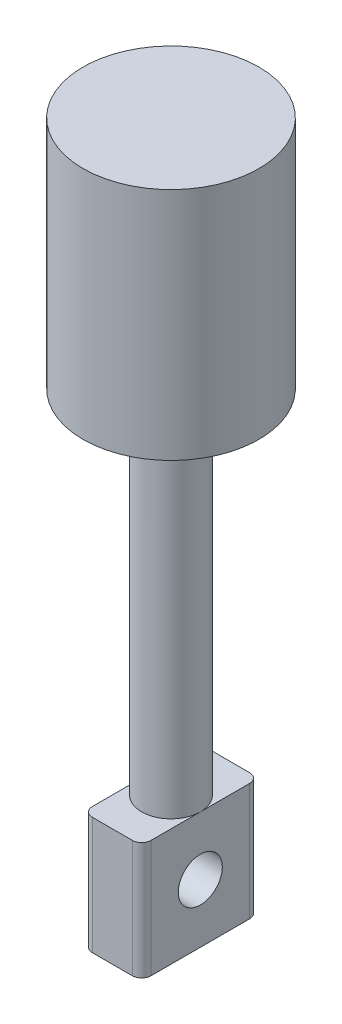
SolidWorks part; units mm, degrees
ref_plane "Front Plane" through (0, 0, 0) normal (0, 0, 1) x (1, 0, 0)
ref_plane "Top Plane" through (0, 0, 0) normal (0, 1, 0) x (1, 0, 0)
ref_plane "Right Plane" through (0, 0, 0) normal (1, 0, 0) x (0, 0, -1)
sketch "Sketch2" plane through (0, 0, 0) normal (0, 1, 0) x (1, 0, 0)
  circle A0 centre (0, 0) radius 4.7625
  dimension "D1" = 9.525
extrude "Boss-Extrude2" add sketch "Sketch2" against normal blind 12.7
sketch "Sketch3" plane through (0, -12.7, 0) normal (0, -1, 0) x (1, 0, 0)
  circle A0 centre (0, 0) radius 1.5875
  dimension "D1" = 3.175
extrude "Boss-Extrude3" add sketch "Sketch3" along normal blind 19.05
sketch "Sketch4" plane through (0, 0, 0) normal (1, 0, 0) x (0, 0, -1)
  line L0 (-1.5875, -31.75) -> (1.5875, -31.75) construction
  line L1 (-3.175, -31.75) -> (3.175, -31.75)
  line L2 (-3.175, -31.75) -> (-3.175, -38.1)
  line L3 (-3.175, -38.1) -> (3.175, -38.1)
  line L4 (3.175, -31.75) -> (3.175, -38.1)
  line L5 (0, -31.75) -> (0, -12.7) construction
  line L6 (-3.175, -34.925) -> (3.7043, -34.925) construction
  line L7 (0, -38.1) -> (0, -31.6236) construction
  circle A0 centre (0, -34.925) radius 1.1906
  point P8 (0, -38.1)
  dimension "D3" = 2.3813
  dimension "D1" = 6.35
  dimension "D2" = 6.35
extrude "Boss-Extrude4" add sketch "Sketch4" along normal mid plane 3.175
fillet "Fillet2" radius 0.508 4 edges at (-1.5875, -34.925, -3.175) (1.5875, -34.925, -3.175) (1.5875, -34.925, 3.175) (-1.5875, -34.925, 3.175)
